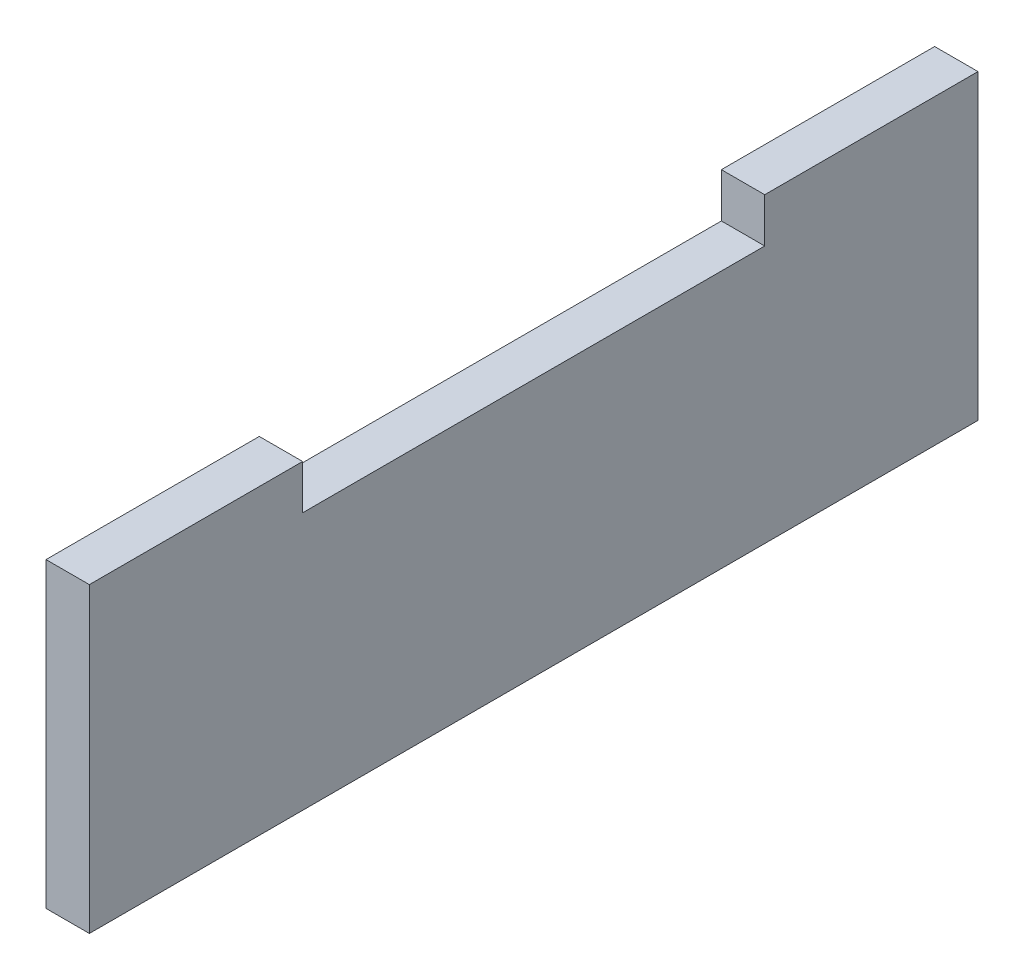
SolidWorks part; units mm, degrees
ref_plane "Front Plane" through (0, 0, 0) normal (0, 0, 1) x (1, 0, 0)
ref_plane "Top Plane" through (0, 0, 0) normal (0, 1, 0) x (1, 0, 0)
ref_plane "Right Plane" through (0, 0, 0) normal (1, 0, 0) x (0, 0, -1)
sketch "Sketch1" plane through (0, 0, 0) normal (1, 0, 0) x (0, 0, -1)
  line L1 (-125, 42.5) -> (125, 42.5)
  line L2 (-125, 42.5) -> (-125, -42.5)
  line L3 (-125, -42.5) -> (125, -42.5)
  line L4 (125, 42.5) -> (125, -42.5)
  line L5 (-125, 42.5) -> (125, -42.5) construction
  line L6 (-125, -42.5) -> (125, 42.5) construction
  line L7 (-65, 42.5) -> (65, 42.5)
  line L8 (-65, 42.5) -> (-65, 30)
  line L9 (-65, 30) -> (65, 30)
  line L10 (65, 42.5) -> (65, 30)
  point P0 (0, 0)
  point P10 (0, 30)
  dimension "D1" = 85
  dimension "D2" = 250
  dimension "D3" = 130
  dimension "D4" = 12.5
extrude "Boss-Extrude1" add sketch "Sketch1" along normal blind 12.2 contours L1 L10 L9 L8 L2 L3 L4
